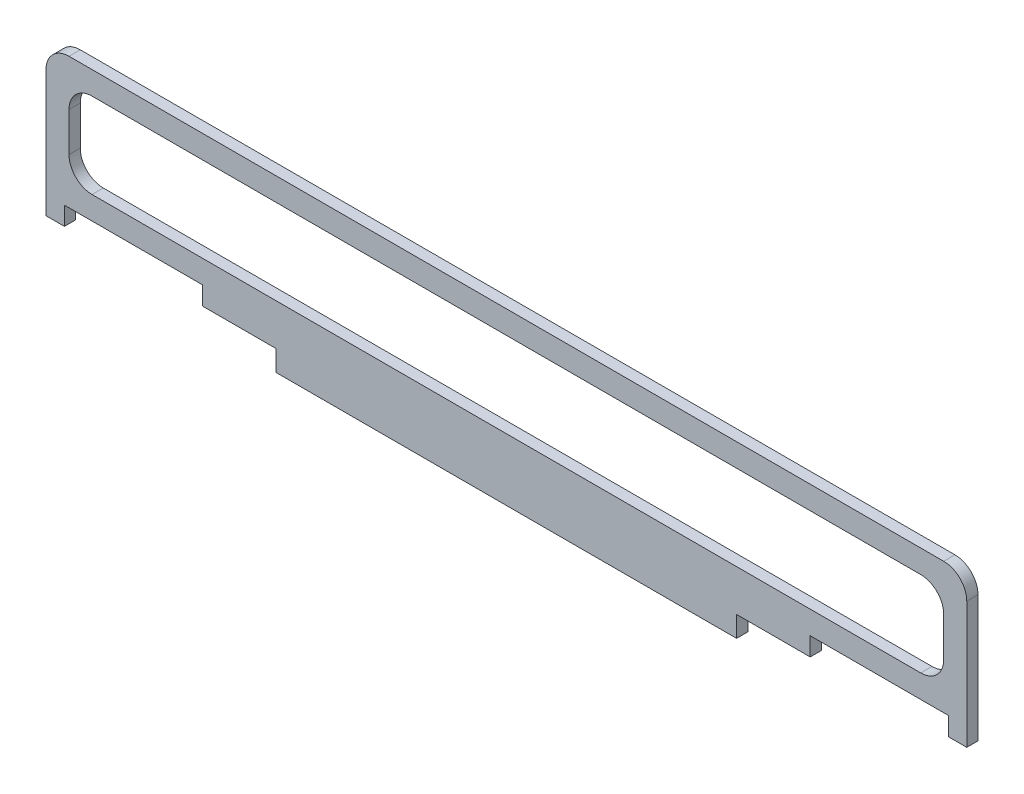
SolidWorks part; units mm, degrees
ref_plane "Front Plane" through (0, 0, 0) normal (0, 0, 1) x (1, 0, 0)
ref_plane "Top Plane" through (0, 0, 0) normal (0, 1, 0) x (1, 0, 0)
ref_plane "Right Plane" through (0, 0, 0) normal (1, 0, 0) x (0, 0, -1)
sketch "Sketch1" plane through (0, 0, 0) normal (0, 0, 1) x (1, 0, 0)
  line L1 (-127, 23.495) -> (127, 23.495)
  line L2 (-127, 23.495) -> (-127, -23.495)
  line L3 (-127, -23.495) -> (127, -23.495)
  line L4 (127, 23.495) -> (127, -23.495)
  line L5 (-127, 23.495) -> (127, -23.495) construction
  line L6 (-127, -23.495) -> (127, 23.495) construction
  point P0 (0, 0)
  dimension "D1" = 46.99
  dimension "D2" = 254
extrude "Boss-Extrude1" add sketch "Sketch1" along normal blind 3.0988
fillet "Fillet1" radius 6.35 2 edges at (127, 23.495, 1.5494) (-127, 23.495, 1.5494)
sketch "Sketch2" plane through (0, 0, 3.0988) normal (0, 0, 1) x (1, 0, 0)
  line L0 (0, -1.7043) -> (0, 1.7043) construction
  line L1 (-127, -23.495) -> (-63.5, -23.495)
  line L2 (-127, -23.495) -> (-127, -17.78)
  line L3 (-127, -17.78) -> (-63.5, -17.78)
  line L4 (-63.5, -23.495) -> (-63.5, -17.78)
  line L5 (63.5, -23.495) -> (63.5, -17.78)
  line L6 (127, -17.78) -> (63.5, -17.78)
  line L7 (127, -23.495) -> (127, -17.78)
  line L8 (127, -23.495) -> (63.5, -23.495)
  dimension "D1" = 63.5
  dimension "D2" = 5.715
extrude "Cut-Extrude1" cut sketch "Sketch2" against normal through all
sketch "Sketch3" plane through (0, 0, 3.0988) normal (0, 0, 1) x (1, 0, 0)
  line L0 (-63.5, -17.78) -> (-127, -17.78) construction
  line L1 (-121.92, -17.78) -> (-83.82, -17.78)
  line L2 (-121.92, -17.78) -> (-121.92, -12.7)
  line L3 (-121.92, -12.7) -> (-83.82, -12.7)
  line L4 (-83.82, -17.78) -> (-83.82, -12.7)
  line L5 (-127, 17.145) -> (-127, -17.78) construction
  line L6 (0, -1.7043) -> (0, 1.7043) construction
  line L7 (83.82, -17.78) -> (83.82, -12.7)
  line L8 (121.92, -12.7) -> (83.82, -12.7)
  line L9 (121.92, -17.78) -> (121.92, -12.7)
  line L10 (121.92, -17.78) -> (83.82, -17.78)
  dimension "D1" = 38.1
  dimension "D2" = 5.08
  dimension "D3" = 5.08
extrude "Cut-Extrude2" cut sketch "Sketch3" against normal through all
sketch "Sketch4" plane through (0, 0, 3.0988) normal (0, 0, 1) x (1, 0, 0)
  line L16 (-77.47, -6.35) -> (77.47, -6.35)
  line L32 (-120.65, -6.35) -> (-77.47, -6.35)
  line L33 (-77.47, -6.35) -> (-77.47, -11.43)
  line L34 (-77.47, -11.43) -> (-57.15, -11.43)
  line L35 (-57.15, -11.43) -> (-57.15, -17.145)
  line L36 (-57.15, -17.145) -> (57.15, -17.145)
  line L37 (57.15, -17.145) -> (57.15, -11.43)
  line L38 (57.15, -11.43) -> (77.47, -11.43)
  line L39 (77.47, -11.43) -> (77.47, -6.35)
  line L40 (77.47, -6.35) -> (120.65, -6.35)
  line L41 (120.65, -6.35) -> (120.65, 17.145)
  line L42 (120.65, 17.145) -> (-120.65, 17.145)
  line L43 (-120.65, 17.145) -> (-120.65, -6.35)
  line L44 (-120.65, -6.35) -> (-77.47, -6.35)
  line L52 (77.47, -6.35) -> (120.65, -6.35)
  line L53 (120.65, -6.35) -> (120.65, 17.145)
  line L54 (120.65, 17.145) -> (-120.65, 17.145)
  line L55 (-120.65, 17.145) -> (-120.65, -6.35)
  dimension "D1" = 6.35
extrude "Cut-Extrude3" cut sketch "Sketch4" against normal through all
fillet "Fillet2" radius 6.35 4 edges at (120.65, -6.35, 1.5494) (120.65, 17.145, 1.5494) (-120.65, 17.145, 1.5494) (-120.65, -6.35, 1.5494)
equation "\"motor offset\"=6mm"
equation "\"thickness0.25\"=0.225in"
equation "\"thickness0.125\"=0.122in"
